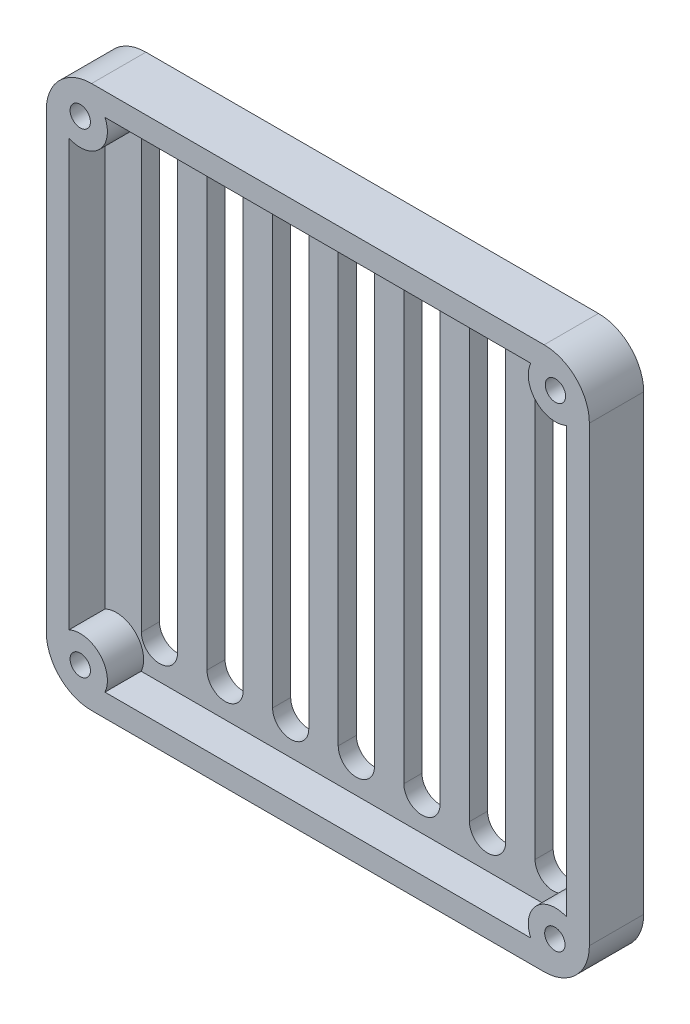
SolidWorks part; units mm, degrees
ref_plane "Front Plane" through (0, 0, 0) normal (0, 0, 1) x (1, 0, 0)
ref_plane "Top Plane" through (0, 0, 0) normal (0, 1, 0) x (1, 0, 0)
ref_plane "Right Plane" through (0, 0, 0) normal (1, 0, 0) x (0, 0, -1)
sketch "Sketch1" plane through (0, 0, 0) normal (0, 0, 1) x (1, 0, 0)
  line L0 (120, 60) -> (-50.3301, 60) construction
  line L1 (0, 0) -> (120, 0)
  line L2 (0, 0) -> (0, 120)
  line L3 (0, 120) -> (120, 120)
  line L4 (120, 0) -> (120, 120)
  line L5 (60, 120) -> (60, 86.5154) construction
  line L6 (7.5, 112.5001) -> (60, 112.5001) construction
  line L7 (60, 112.5001) -> (112.5, 112.5001) construction
  line L8 (112.5, 112.5001) -> (112.5, 60) construction
  line L9 (112.5, 60) -> (112.3733, 7.5001) construction
  circle A0 centre (7.5, 112.5001) radius 2.25
  circle A1 centre (112.5, 112.5001) radius 2.25
  circle A2 centre (7.5, 7.5001) radius 2.25
  circle A3 centre (112.3733, 7.5001) radius 2.25
  point P19 (25.6172, 9.7573)
  point P20 (0, 0)
  point P21 (0, 0)
  point P22 (0, 0)
  dimension "D2" = 4.5
  dimension "D3" = 4.5
  dimension "D4" = 4.5
  dimension "D5" = 4.5
  dimension "D7" = 105
  dimension "D1" = 120
  dimension "D6" = 105
extrude "Boss-Extrude1" add sketch "Sketch1" along normal blind 4
fillet "Fillet1" radius 10 4 edges at (0, 0, 2) (120, 0, 2) (120, 120, 2) (0, 120, 2)
sketch "Sketch2" plane through (0, 0, 4) normal (0, 0, 1) x (1, 0, 0)
  line L0 (5, 107.0457) -> (5, 12.9543)
  line L1 (12.9544, 5) -> (107.0456, 5)
  line L2 (115, 12.9543) -> (115, 107.0457)
  line L3 (107.0456, 115) -> (12.9544, 115)
  line L4 (0, 110) -> (0, 10)
  line L5 (10, 0) -> (110, 0)
  line L6 (120, 10) -> (120, 110)
  line L7 (110, 120) -> (10, 120)
  line L8 (0, 110) -> (0, 10)
  line L9 (10, 0) -> (110, 0)
  line L10 (120, 10) -> (120, 110)
  line L11 (110, 120) -> (10, 120)
  line L12 (60, 120) -> (60, 126.8445) construction
  line L13 (120, 60) -> (135.2428, 60) construction
  line L15 (5, 110) -> (5, 10) construction
  line L16 (110, 115) -> (10, 115) construction
  line L17 (115, 10) -> (115, 110) construction
  line L18 (10, 5) -> (110, 5) construction
  circle A0 centre (7.5, 7.5001) radius 2.25 construction
  circle A1 centre (112.3733, 7.5001) radius 2.25 construction
  circle A2 centre (112.5, 112.5001) radius 2.25 construction
  circle A3 centre (7.5, 112.5001) radius 2.25 construction
  arc A4 (0, 10) -> (10, 0) centre (10, 10) ccw
  arc A5 (110, 0) -> (120, 10) centre (110, 10) ccw
  arc A6 (120, 110) -> (110, 120) centre (110, 110) ccw
  arc A7 (10, 120) -> (0, 110) centre (10, 110) ccw
  arc A8 (0, 10) -> (10, 0) centre (10, 10) ccw
  arc A9 (110, 0) -> (120, 10) centre (110, 10) ccw
  arc A10 (120, 110) -> (110, 120) centre (110, 110) ccw
  arc A11 (10, 120) -> (0, 110) centre (10, 110) ccw
  arc A12 (5, 107.0457) -> (12.9544, 115) centre (7.5, 112.5001) ccw
  arc A13 (5, 12.9543) -> (12.9544, 5) centre (7.5, 7.4999) cw
  arc A14 (115, 12.9543) -> (107.0456, 5) centre (112.5, 7.4999) ccw
  arc A15 (115, 107.0457) -> (107.0456, 115) centre (112.5, 112.5001) cw
  arc A16 (10, 115) -> (5, 110) centre (10, 110) ccw construction
  arc A17 (115, 110) -> (110, 115) centre (110, 110) ccw construction
  arc A18 (110, 5) -> (115, 10) centre (110, 10) ccw construction
  arc A19 (5, 10) -> (10, 5) centre (10, 10) ccw construction
  circle A20 centre (7.5, 7.5001) radius 2.25
  circle A21 centre (112.3733, 7.5001) radius 2.25
  circle A22 centre (112.5, 112.5001) radius 2.25
  circle A23 centre (7.5, 112.5001) radius 2.25
  dimension "D3" = 12
  dimension "D1" = 0
  dimension "D2" = 5
extrude "Boss-Extrude2" add sketch "Sketch2" along normal blind 8
sketch "Sketch3" plane through (0, 0, 0) normal (0, 0, -1) x (-1, 0, 0)
  line L0 (-104, 107.5) -> (-104, 12.5) construction
  line L1 (-100, 107.5) -> (-100, 12.5)
  line L2 (-108, 107.5) -> (-108, 12.5)
  line L4 (-104, 12.5) -> (-104, 0) construction
  line L5 (-10, 0) -> (-110, 0) construction
  line L6 (-104, 107.5) -> (-104, 120) construction
  line L7 (-110, 120) -> (-10, 120) construction
  line L9 (-89.5, 107.5) -> (-89.5, 12.5) construction
  line L10 (-85.5, 107.5) -> (-85.5, 12.5)
  line L11 (-93.5, 107.5) -> (-93.5, 12.5)
  line L12 (-75, 107.5) -> (-75, 12.5) construction
  line L13 (-71, 107.5) -> (-71, 12.5)
  line L14 (-79, 107.5) -> (-79, 12.5)
  line L15 (-60.5, 107.5) -> (-60.5, 12.5) construction
  line L16 (-56.5, 107.5) -> (-56.5, 12.5)
  line L17 (-64.5, 107.5) -> (-64.5, 12.5)
  line L18 (-46, 107.5) -> (-46, 12.5) construction
  line L19 (-42, 107.5) -> (-42, 12.5)
  line L20 (-50, 107.5) -> (-50, 12.5)
  line L21 (-31.5, 107.5) -> (-31.5, 12.5) construction
  line L22 (-27.5, 107.5) -> (-27.5, 12.5)
  line L23 (-35.5, 107.5) -> (-35.5, 12.5)
  line L24 (-17, 107.5) -> (-17, 12.5) construction
  line L25 (-13, 107.5) -> (-13, 12.5)
  line L26 (-21, 107.5) -> (-21, 12.5)
  arc A0 (-100, 107.5) -> (-108, 107.5) centre (-104, 107.5) ccw
  arc A1 (-108, 12.5) -> (-100, 12.5) centre (-104, 12.5) ccw
  arc A2 (-85.5, 107.5) -> (-93.5, 107.5) centre (-89.5, 107.5) ccw
  arc A3 (-93.5, 12.5) -> (-85.5, 12.5) centre (-89.5, 12.5) ccw
  arc A4 (-71, 107.5) -> (-79, 107.5) centre (-75, 107.5) ccw
  arc A5 (-79, 12.5) -> (-71, 12.5) centre (-75, 12.5) ccw
  arc A6 (-56.5, 107.5) -> (-64.5, 107.5) centre (-60.5, 107.5) ccw
  arc A7 (-64.5, 12.5) -> (-56.5, 12.5) centre (-60.5, 12.5) ccw
  arc A8 (-42, 107.5) -> (-50, 107.5) centre (-46, 107.5) ccw
  arc A9 (-50, 12.5) -> (-42, 12.5) centre (-46, 12.5) ccw
  arc A10 (-27.5, 107.5) -> (-35.5, 107.5) centre (-31.5, 107.5) ccw
  arc A11 (-35.5, 12.5) -> (-27.5, 12.5) centre (-31.5, 12.5) ccw
  arc A12 (-13, 107.5) -> (-21, 107.5) centre (-17, 107.5) ccw
  arc A13 (-21, 12.5) -> (-13, 12.5) centre (-17, 12.5) ccw
  point P2 (-104, 60)
  point P18 (-89.5, 60)
  point P25 (-75, 60)
  point P32 (-60.5, 60)
  point P39 (-46, 60)
  point P46 (-31.5, 60)
  point P53 (-17, 60)
  dimension "D1" = 8
  dimension "D2" = 7
  dimension "D3" = 95
extrude "Cut-Extrude1" cut sketch "Sketch3" against normal blind 8
